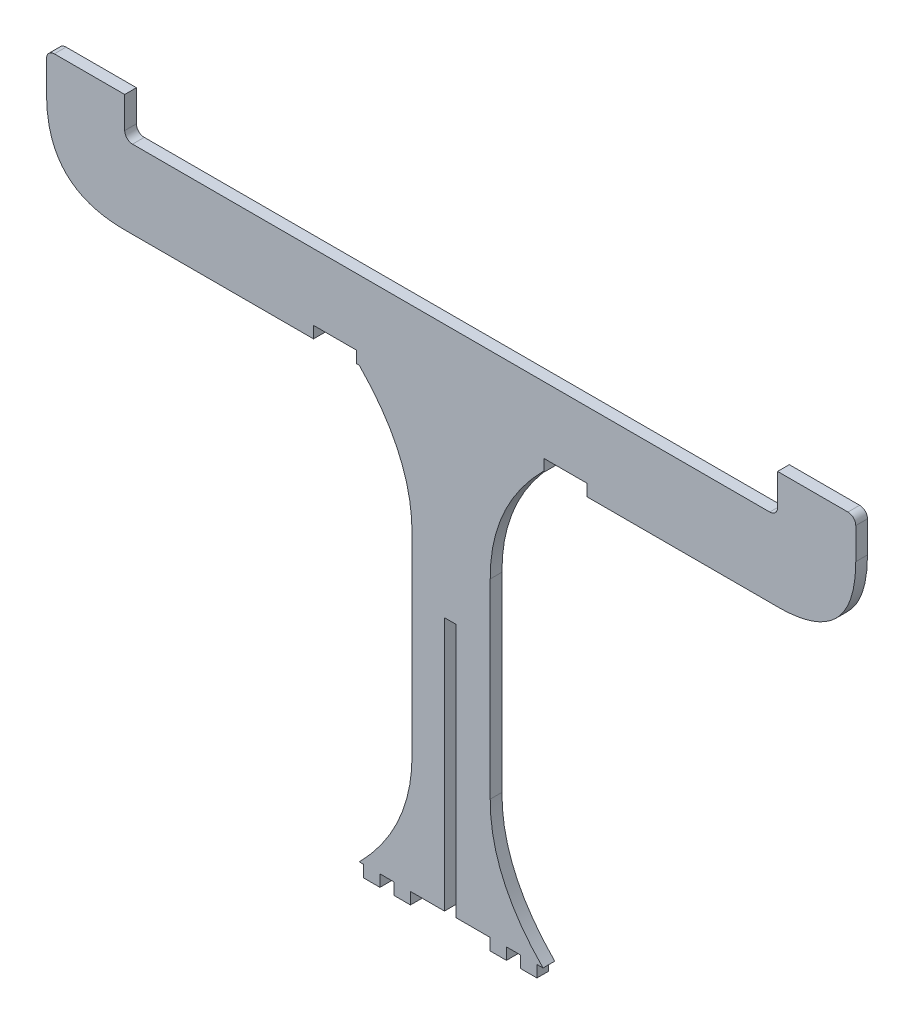
SolidWorks part; units mm, degrees
ref_plane "Přední rovina" through (0, 0, 0) normal (0, 0, 1) x (1, 0, 0)
ref_plane "Horní rovina" through (0, 0, 0) normal (0, 1, 0) x (1, 0, 0)
ref_plane "Pravá rovina" through (0, 0, 0) normal (1, 0, 0) x (0, 0, -1)
sketch "Skica1" plane through (0, 0, 0) normal (0, 0, 1) x (1, 0, 0)
  line L0 (-30.6426, 2.6943) -> (16.3574, 2.6943)
  line L1 (-7.1426, 2.6943) -> (-7.1426, -107.3057)
  line L2 (16.3574, -107.3057) -> (-30.6426, -107.3057)
  line L3 (-17.1426, 9.0001) -> (-17.1426, -176.0586) construction
  line L4 (27.2473, -27.3057) -> (-64.2445, -27.3057) construction
  line L5 (15.3668, -77.3057) -> (-64.2445, -77.3057) construction
  line L6 (-17.1426, -27.8784) -> (-17.1426, -76.656)
  line L7 (2.8574, -27.8784) -> (2.8574, -76.656)
  line L24 (-7.1426, -15.139) -> (-7.1426, 72.526) construction
  line L25 (10.652, -107.3057) -> (10.652, -110.3057)
  line L26 (10.652, -107.3057) -> (14.802, -107.3057)
  line L27 (14.802, -107.3057) -> (14.802, -110.3057)
  line L28 (10.652, -110.3057) -> (14.802, -110.3057)
  line L29 (2.852, -107.3057) -> (2.852, -110.3057)
  line L30 (2.852, -107.3057) -> (7.002, -107.3057)
  line L31 (7.002, -107.3057) -> (7.002, -110.3057)
  line L32 (2.852, -110.3057) -> (7.002, -110.3057)
  line L33 (-25.348, -110.3057) -> (-29.498, -110.3057)
  line L34 (-29.498, -107.3057) -> (-29.498, -110.3057)
  line L35 (-25.348, -107.3057) -> (-29.498, -107.3057)
  line L36 (-25.348, -107.3057) -> (-25.348, -110.3057)
  line L37 (-17.548, -110.3057) -> (-21.698, -110.3057)
  line L38 (-21.698, -107.3057) -> (-21.698, -110.3057)
  line L39 (-17.548, -107.3057) -> (-21.698, -107.3057)
  line L40 (-17.548, -107.3057) -> (-17.548, -110.3057)
  line L41 (-190.6426, 2.6943) -> (100.2644, 2.6943) construction
  line L42 (16.3574, 2.6943) -> (16.3574, 73.8241) construction
  line L43 (-30.6426, 73.8241) -> (-30.6426, 2.6943) construction
  line L44 (-110.6426, 2.6943) -> (-110.6426, 52.9232) construction
  line L45 (-190.6426, 32.6943) -> (86.9117, 32.6943) construction
  line L46 (-30.6426, 2.6943) -> (-90.6426, 2.6943)
  line L47 (-90.6426, -13.7924) -> (-90.6426, 96.8534) construction
  line L48 (-70.6426, -7.8313) -> (-70.6426, 84.4343) construction
  line L49 (-194.5635, 22.6943) -> (-7.1426, 22.6943) construction
  line L50 (-108.6426, 32.6943) -> (-90.6426, 32.6943)
  line L51 (-90.6426, 32.6943) -> (-90.6426, 24.6943)
  line L52 (-110.6426, 22.6943) -> (-110.6426, 30.6943)
  line L53 (16.3574, 2.6943) -> (76.3574, 2.6943)
  line L54 (-110.6426, 22.6943) -> (-110.6426, 2.6943) construction
  line L55 (76.3574, 32.6943) -> (76.3574, 24.6943)
  line L56 (-110.6426, 2.6943) -> (-90.6426, 2.6943) construction
  line L57 (94.3574, 32.6943) -> (76.3574, 32.6943)
  line L58 (-88.6426, 22.6943) -> (74.3574, 22.6943)
  line L59 (-7.1426, 22.6943) -> (-7.1426, 2.6943)
  line L60 (96.3574, 22.6943) -> (96.3574, 30.6943)
  line L61 (96.3574, 22.6943) -> (96.3574, 2.6943) construction
  line L62 (96.3574, 2.6943) -> (76.3574, 2.6943) construction
  arc A0 (74.3574, 22.6943) -> (76.3574, 24.6943) centre (74.3574, 24.6943) ccw
  arc A1 (-88.6426, 22.6943) -> (-90.6426, 24.6943) centre (-88.6426, 24.6943) cw
  arc A2 (-110.6426, 30.6943) -> (-108.6426, 32.6943) centre (-108.6426, 30.6943) cw
  arc A3 (96.3574, 30.6943) -> (94.3574, 32.6943) centre (94.3574, 30.6943) ccw
  spline S0 degree 2 poles (-30.6426, 2.6943) (-17.0251, -11.1181) (-17.1426, -27.8784) knots 0 0 0 1 1 1
  spline S1 degree 2 poles (-30.6426, -107.3057) (-17.0093, -93.4583) (-17.1426, -76.656) knots 0 0 0 1 1 1
  spline S2 degree 2 poles (16.3574, 2.6943) (2.7399, -11.1181) (2.8574, -27.8784) knots 0 0 0 1 1 1
  spline S3 degree 2 poles (16.3574, -107.3057) (2.724, -93.4583) (2.8574, -76.656) knots 0 0 0 1 1 1
  spline S4 degree 2 poles (-110.6426, 22.6943) (-110.6426, 2.6943) (-90.6426, 2.6943) knots 0 0 0 1 1 1
  spline S5 degree 2 poles (96.3574, 22.6943) (96.3574, 2.6943) (76.3574, 2.6943) knots 0 0 0 1 1 1
  point P37 (-110.6426, 22.6943)
  point P54 (-110.6426, 32.6943)
  point P55 (-90.6426, 32.6943)
  point P56 (-90.6426, 22.6943)
  point P70 (-90.6426, 22.6943)
  point P73 (-110.6426, 32.6943)
  dimension "D15" = 60
  dimension "D17" = 2
  dimension "D18" = 2
  dimension "D1" = 110
  dimension "D2" = 23.5
  dimension "D3" = 30
  dimension "D4" = 30
  dimension "D5" = 30.6498
  dimension "D6" = 23.5
  dimension "D7" = 47
  dimension "D8" = 30
  dimension "D9" = 30
  dimension "D10" = 20
  dimension "D11" = 80
  dimension "D12" = 20
  dimension "D13" = 40
  dimension "D14" = 10
extrude "Přidat vysunutím2" add sketch "Skica1" along normal blind 3
sketch "Skica2" plane through (0, 0, 0) normal (0, 0, -1) x (-1, 0, 0)
  line L0 (7.348, -179.4639) -> (7.348, -1.6157) construction
  line L1 (50.2587, -107.3057) -> (-73.7805, -107.3057) construction
  line L2 (-2.852, -107.3057) -> (17.548, -107.3057) construction
  line L5 (8.848, -107.3057) -> (5.848, -107.3057)
  line L8 (8.848, -42.3057) -> (5.848, -42.3057)
  line L9 (8.848, -42.3057) -> (8.848, -107.3057)
  line L10 (8.848, -107.3057) -> (5.848, -107.3057)
  line L11 (5.848, -42.3057) -> (5.848, -107.3057)
  line L12 (8.848, -42.3057) -> (5.848, -107.3057) construction
  line L13 (8.848, -107.3057) -> (5.848, -42.3057) construction
  line L15 (88.6426, 22.6943) -> (-74.3574, 22.6943) construction
  point P5 (7.348, -134.9898)
  point P8 (7.348, -74.8057)
  dimension "D1" = 130
  dimension "D2" = 65
  dimension "D4" = 3
  dimension "D5" = 3
extrude "Odebrat vysunutím3" cut sketch "Skica2" against normal blind 3 contours L11 L10 L9 L8
sketch "Skica3" plane through (0, 0, 0) normal (0, 0, -1) x (-1, 0, 0)
  line L0 (7.348, -42.3057) -> (7.348, -114.178) construction
  line L1 (8.848, -42.3057) -> (5.848, -42.3057) construction
  line L2 (97.3892, 0) -> (-87.6269, 0) construction
  line L3 (-16.3574, 2.6943) -> (-76.3574, 2.6943) construction
  line L4 (-27.652, 0) -> (-16.652, 0)
  line L5 (-27.652, 0) -> (-27.652, 5.6943)
  line L6 (-27.652, 5.6943) -> (-16.652, 5.6943)
  line L7 (-16.652, 0) -> (-16.652, 5.6943)
  line L8 (42.348, 5.6943) -> (31.348, 5.6943)
  line L9 (31.348, 0) -> (31.348, 5.6943)
  line L10 (42.348, 0) -> (31.348, 0)
  line L11 (42.348, 0) -> (42.348, 5.6943)
  dimension "D1" = 24
  dimension "D2" = 35
  dimension "D3" = 3
extrude "Odebrat vysunutím4" cut sketch "Skica3" against normal blind 3
